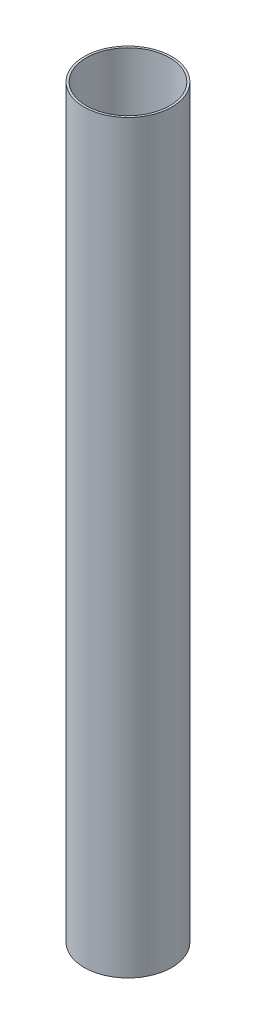
SolidWorks part; units mm, degrees
ref_plane "Front Plane" through (0, 0, 0) normal (0, 0, 1) x (1, 0, 0)
ref_plane "Top Plane" through (0, 0, 0) normal (0, 1, 0) x (1, 0, 0)
ref_plane "Right Plane" through (0, 0, 0) normal (1, 0, 0) x (0, 0, -1)
sketch "Sketch1" plane through (0, 0, 0) normal (0, 1, 0) x (1, 0, 0)
  circle A0 centre (0, 0) radius 41.15
  circle A1 centre (0, 0) radius 39.15
  dimension "D1" = 82.3
  dimension "D2" = 78.3
extrude "Boss-Extrude1" add sketch "Sketch1" along normal blind 700
